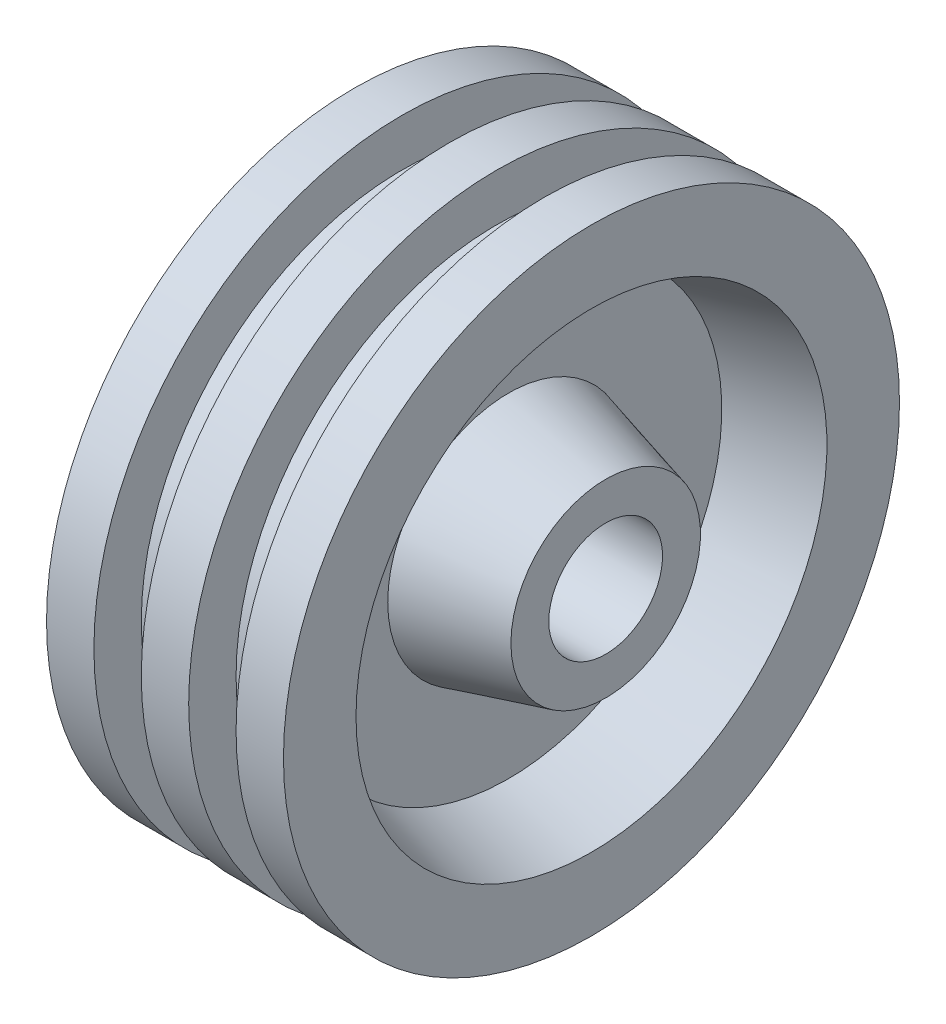
SolidWorks part; units mm, degrees
material "1060 Сплав"
ref_plane "Спереди" through (0, 0, 0) normal (0, 0, 1) x (1, 0, 0)
ref_plane "Сверху" through (0, 0, 0) normal (0, 1, 0) x (1, 0, 0)
ref_plane "Справа" through (0, 0, 0) normal (1, 0, 0) x (0, 0, -1)
sketch "Эскиз1" plane through (0, 0, 0) normal (0, 0, 1) x (1, 0, 0)
  line L0 (-926.2866, 0) -> (45388.0416, 0) construction
  line L1 (0, -926.2866) -> (0, 45388.0416) construction
  line L2 (0, 65) -> (0, 49.6891)
  line L3 (0, 49.6891) -> (17.5, 45)
  line L4 (17.5, 45) -> (17.5, 20)
  line L5 (17.5, 20) -> (13, 20)
  line L6 (13, 20) -> (13, 12)
  line L7 (13, 12) -> (53, 12)
  line L8 (53, 12) -> (53, 20)
  line L9 (53, 20) -> (32.5, 25.493)
  line L10 (32.5, 25.493) -> (32.5, 45)
  line L11 (32.5, 45) -> (50, 49.6891)
  line L12 (50, 49.6891) -> (50, 65)
  line L13 (50, 65) -> (40, 65)
  line L14 (40, 65) -> (40, 55)
  line L15 (40, 55) -> (30, 55)
  line L16 (30, 55) -> (30, 65)
  line L17 (30, 65) -> (20, 65)
  line L18 (20, 65) -> (20, 55)
  line L19 (20, 55) -> (10, 55)
  line L20 (10, 55) -> (10, 65)
  line L21 (10, 65) -> (0, 65)
  dimension "D1" = 10
  dimension "D2" = 4.5
  dimension "D3" = 20.5
  dimension "D4" = 15
  dimension "D5" = 12
  dimension "D6" = 20
  dimension "D7" = 45
  dimension "D8" = 15
  dimension "D9" = 15
  dimension "D10" = 45
  dimension "D11" = 65
  dimension "D12" = 17.5
  dimension "D13" = 20
revolve "Повернуть1" add sketch "Эскиз1" angle 360 about L0
